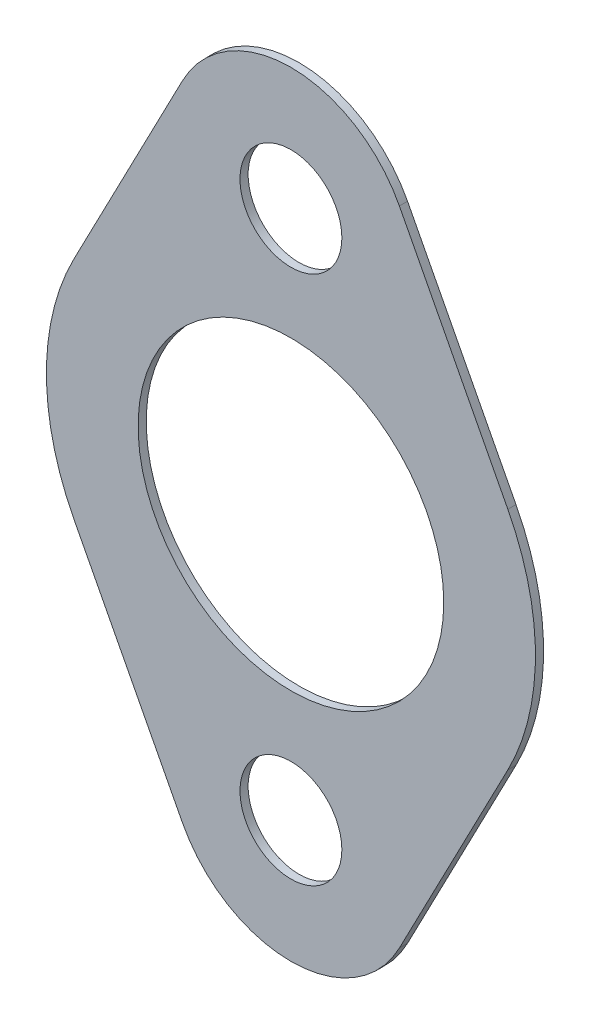
SolidWorks part; units mm, degrees
material "PW20:29:Sc:0:"
ref_plane "Front" through (0, 0, 0) normal (0, 0, 1) x (1, 0, 0)
ref_plane "Top" through (0, 0, 0) normal (0, 1, 0) x (1, 0, 0)
ref_plane "Right" through (0, 0, 0) normal (1, 0, 0) x (0, 0, -1)
sketch "Sketch1" plane through (0, 0, 0) normal (0, 0, 1) x (1, 0, 0)
  line L0 (0, 0) -> (0, 94.4945) construction
  line L1 (0, 0) -> (88.837, 0) construction
  line L2 (26.6136, 78.8462) -> (53.2272, 27.6923)
  line L3 (26.6136, -78.8462) -> (53.2272, -27.6923)
  line L4 (-26.6136, 78.8462) -> (-53.2272, 27.6923)
  line L5 (-26.6136, -78.8462) -> (-53.2272, -27.6923)
  arc A0 (-26.6136, 78.8462) -> (26.6136, 78.8462) centre (0, 65) cw
  arc A1 (-26.6136, -78.8462) -> (26.6136, -78.8462) centre (0, -65) ccw
  arc A2 (53.2272, 27.6923) -> (53.2272, -27.6923) centre (0, 0) cw
  arc A3 (-53.2272, -27.6923) -> (-53.2272, 27.6923) centre (0, 0) cw
  dimension "EndR" = 30
  dimension "SideR" = 60
  dimension "CtoC" = 130
extrude "Main" add sketch "Sketch1" along normal blind 2
sketch "Sketch2" plane through (0, 0, 2) normal (0, 0, 1) x (1, 0, 0)
  circle A0 centre (0, 65) radius 12.5
  circle A1 centre (0, -65) radius 12.5
  circle A2 centre (0, 0) radius 37.5
  dimension "BoltH" = 25
  dimension "CenterH" = 75
extrude "Holes" cut sketch "Sketch2" against normal through all
